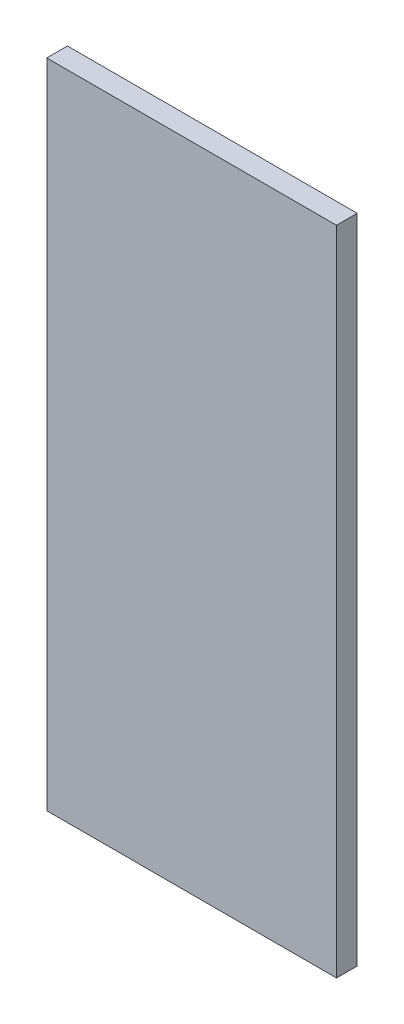
SolidWorks part; units mm, degrees
ref_plane "Front Plane" through (0, 0, 0) normal (0, 0, 1) x (1, 0, 0)
ref_plane "Top Plane" through (0, 0, 0) normal (0, 1, 0) x (1, 0, 0)
ref_plane "Right Plane" through (0, 0, 0) normal (1, 0, 0) x (0, 0, -1)
sketch "Sketch1" plane through (0, 0, 0) normal (0, 0, 1) x (1, 0, 0)
  line L1 (0, 0) -> (88.9, 0)
  line L2 (0, 0) -> (0, 200)
  line L3 (0, 200) -> (88.9, 200)
  line L4 (88.9, 0) -> (88.9, 200)
  dimension "D1" = 88.9
  dimension "D2" = 200
extrude "Boss-Extrude1" add sketch "Sketch1" along normal blind 6.35
